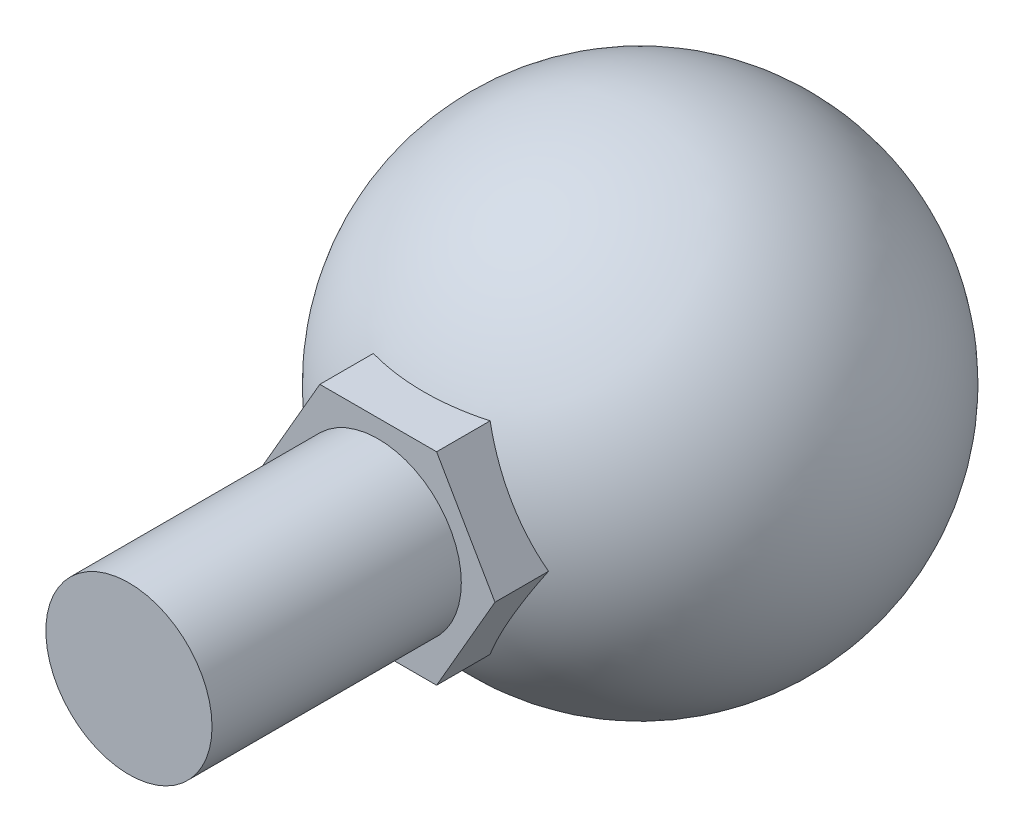
SolidWorks part; units mm, degrees
ref_plane "Front Plane" through (0, 0, 0) normal (0, 0, 1) x (1, 0, 0)
ref_plane "Top Plane" through (0, 0, 0) normal (0, 1, 0) x (1, 0, 0)
ref_plane "Right Plane" through (0, 0, 0) normal (1, 0, 0) x (0, 0, -1)
sketch "Sketch1" plane through (0, 0, 0) normal (0, 1, 0) x (1, 0, 0)
  line L0 (0, -11.5) -> (0, 11.5)
  arc A0 (0, 11.5) -> (0, -11.5) centre (0, 0) ccw
  point P6 (0, 0)
  dimension "D1" = 23
revolve "Revolve1" add sketch "Sketch1" angle 360 about L0
sketch "Sketch2" plane through (0, 0, 0) normal (0, 1, 0) x (1, 0, 0)
  line L0 (0, -9.6101) -> (-4, -9.6101)
  line L1 (-4, -9.6101) -> (-4, -24.6101)
  line L2 (-4, -24.6101) -> (0, -24.6101)
  line L3 (0, -24.6101) -> (0, -9.6101)
  dimension "D1" = 4
  dimension "D2" = 15
revolve "Revolve2" add sketch "Sketch2" angle 360 about L3
ref_plane "Plane1" through (0, 0, 9.6101) normal (0, 0, 1) x (1, 0, 0)
sketch "Sketch3" plane through (0, 0, 9.6101) normal (0, 0, 1) x (1, 0, 0)
  line L1 (2.8103, 4.8675) -> (-2.8103, 4.8675)
  line L2 (-2.8103, 4.8675) -> (-5.6206, 0)
  line L3 (-5.6206, 0) -> (-2.8103, -4.8675)
  line L4 (-2.8103, -4.8675) -> (2.8103, -4.8675)
  line L5 (2.8103, -4.8675) -> (5.6206, 0)
  line L6 (5.6206, 0) -> (2.8103, 4.8675)
  circle A0 centre (0, 0) radius 4.8675 construction
extrude "Boss-Extrude1" add sketch "Sketch3" along normal blind 3
